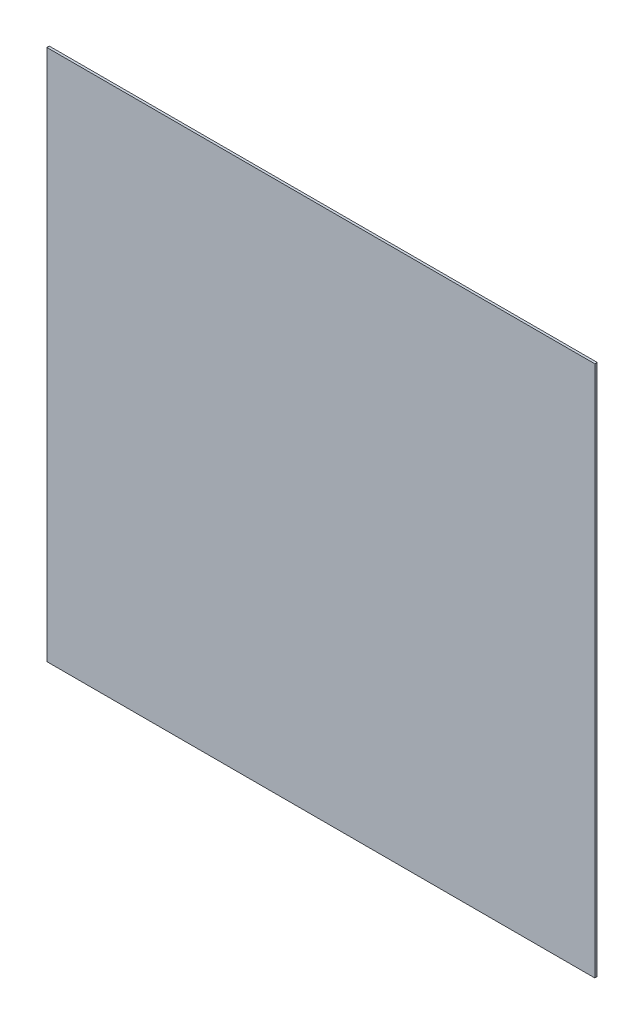
SolidWorks part; units mm, degrees
material "AISI 4130 Steel, normalized at 870C"
ref_plane "Front Plane" through (0, 0, 0) normal (0, 0, 1) x (1, 0, 0)
ref_plane "Top Plane" through (0, 0, 0) normal (0, 1, 0) x (1, 0, 0)
ref_plane "Right Plane" through (0, 0, 0) normal (1, 0, 0) x (0, 0, -1)
sketch "Sketch2" plane through (0, 0, 0) normal (0, 0, 1) x (1, 0, 0)
  line L1 (-170, 165) -> (170, 165)
  line L2 (-170, 165) -> (-170, -165)
  line L3 (-170, -165) -> (170, -165)
  line L4 (170, 165) -> (170, -165)
  dimension "D1" = 340
  dimension "D2" = 330
  dimension "D3" = 165
  dimension "D4" = 170
extrude "Boss-Extrude2" add sketch "Sketch2" along normal blind 1.5
